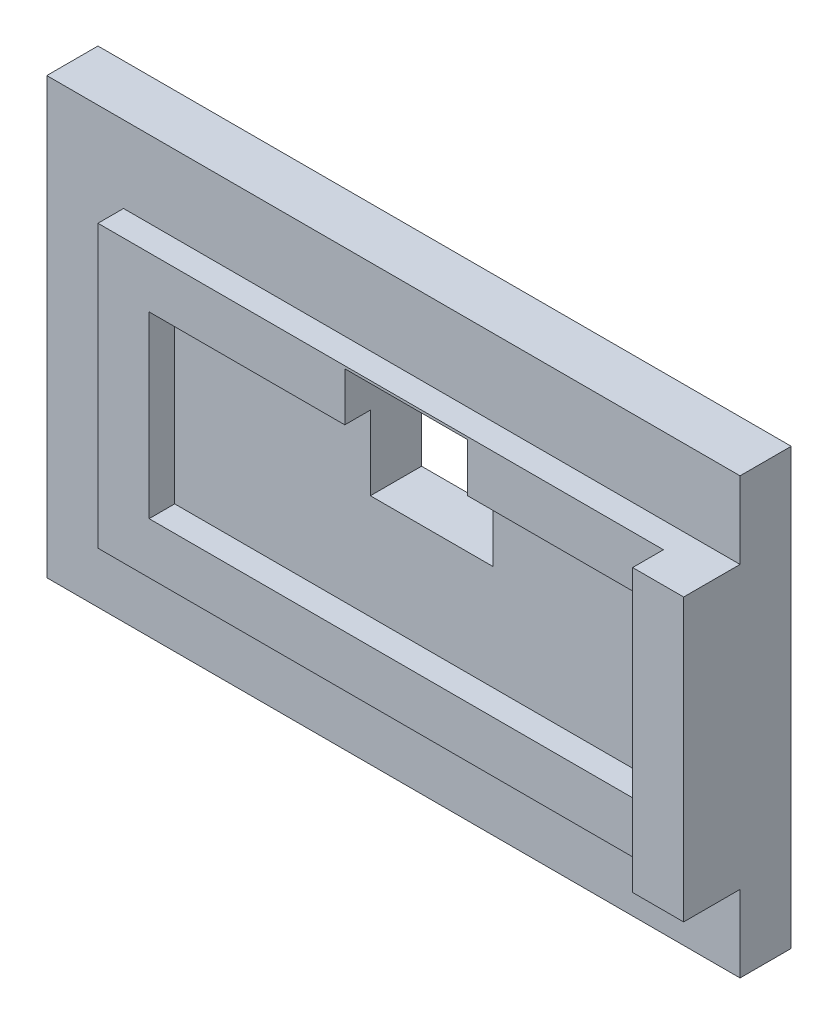
SolidWorks part; units mm, degrees
material "Polyurethane Foam Rigid"
ref_plane "X-Y Datum" through (0, 0, 0) normal (0, 0, 1) x (1, 0, 0)
ref_plane "X-Z Datum" through (0, 0, 0) normal (0, 1, 0) x (1, 0, 0)
ref_plane "Y-Z Datum" through (0, 0, 0) normal (1, 0, 0) x (0, 0, -1)
sketch "Sketch1" plane through (0, 0, 0) normal (0, 0, 1) x (1, 0, 0)
  line L0 (-127.6248, -82.55) -> (-127.6248, 82.55)
  line L1 (-153.0248, -107.95) -> (153.0248, -107.95)
  line L2 (-153.0248, -107.95) -> (-153.0248, 107.95)
  line L3 (-153.0248, 107.95) -> (153.0248, 107.95)
  line L4 (153.0248, -107.95) -> (153.0248, 107.95)
  line L5 (-153.0248, -107.95) -> (153.0248, 107.95) construction
  line L6 (-153.0248, 107.95) -> (153.0248, -107.95) construction
  line L7 (-127.6248, 82.55) -> (127.6248, 82.55)
  line L8 (127.6248, -82.55) -> (127.6248, 82.55)
  line L9 (-127.6248, -82.55) -> (127.6248, -82.55)
  point P0 (0, 0)
  dimension "D1" = 306.0497
  dimension "D2" = 215.9
  dimension "D3" = 25.4
extrude "Boss-Extrude1" add sketch "Sketch1" along normal blind 25.4 contours L0 L9 L8 L7 | L1 L4 L3 L2 L9 L0 L7 L8
sketch "Sketch10" plane through (0, 0, 25.4) normal (0, 0, 1) x (1, 0, 0)
  line L0 (153.0248, -107.95) -> (153.0248, 107.95) construction
  line L1 (-153.0248, -69.8498) -> (153.0248, -69.8498)
  line L2 (-153.0248, -69.8498) -> (-153.0248, 69.8498)
  line L3 (-153.0248, 69.8498) -> (153.0248, 69.8498)
  line L4 (153.0248, -69.8498) -> (153.0248, 69.8498)
  line L5 (-153.0248, -69.8498) -> (153.0248, 69.8498) construction
  line L6 (-153.0248, 69.8498) -> (153.0248, -69.8498) construction
  line L7 (-127.6248, 44.4498) -> (127.6248, 44.4498)
  line L8 (127.6248, -44.4498) -> (127.6248, 44.4498)
  line L9 (-127.6248, -44.4498) -> (127.6248, -44.4498)
  line L10 (-127.6248, -44.4498) -> (-127.6248, 44.4498)
  point P0 (0, 0)
  dimension "D2" = 139.6996
  dimension "D1" = 25.4
extrude "Boss-Extrude6" add sketch "Sketch10" along normal blind 12.7
sketch "Sketch12" plane through (0, 0, 38.1) normal (0, 0, 1) x (1, 0, 0)
  line L0 (153.0248, 69.8498) -> (-153.0248, 69.8498) construction
  line L1 (153.0248, -69.8498) -> (127.6968, -69.8498)
  line L2 (153.0248, -69.8498) -> (153.0248, 69.8498)
  line L3 (153.0248, 69.8498) -> (127.6968, 69.8498)
  line L4 (127.6968, -69.8498) -> (127.6968, 69.8498)
  line L5 (153.0248, -69.8498) -> (127.6968, 69.8498) construction
  line L6 (153.0248, 69.8498) -> (127.6968, -69.8498) construction
  point P4 (140.3608, 0)
  dimension "D1" = 25.328
extrude "Boss-Extrude7" add sketch "Sketch12" along normal blind 15.301
sketch "Sketch14" plane through (0, 0, 0) normal (0, 0, -1) x (-1, 0, 0)
  line L0 (-153.0248, -107.95) -> (-153.0248, 107.95) construction
  line L2 (-30.48, 7.62) -> (30.48, 7.62)
  line L3 (-30.48, 7.62) -> (-30.48, 68.58)
  line L4 (-30.48, 68.58) -> (30.48, 68.58)
  line L5 (30.48, 7.62) -> (30.48, 68.58)
  line L6 (-30.48, 7.62) -> (30.48, 68.58) construction
  line L7 (-30.48, 68.58) -> (30.48, 7.62) construction
  point P3 (0, 38.1)
  dimension "D1" = 60.96
  dimension "D2" = 60.96
  dimension "D3" = 153.0248
  dimension "D4" = 38.1
extrude "Cut-Extrude1" cut sketch "Sketch14" against normal through all
sketch "Sketch5" plane through (-153.0248, 0, 0) normal (-1, 0, 0) x (0, 0, 1)
  line L1 (0, 107.95) -> (25.4, 107.95)
  line L2 (0, 107.95) -> (0, -107.95)
  line L3 (0, -107.95) -> (25.4, -107.95)
  line L4 (25.4, 107.95) -> (25.4, -107.95)
  line L5 (0, 107.95) -> (25.4, -107.95) construction
  line L6 (0, -107.95) -> (25.4, 107.95) construction
  point P4 (12.7, 0)
extrude "Boss-Extrude4" add sketch "Sketch5" along normal blind 38.1
